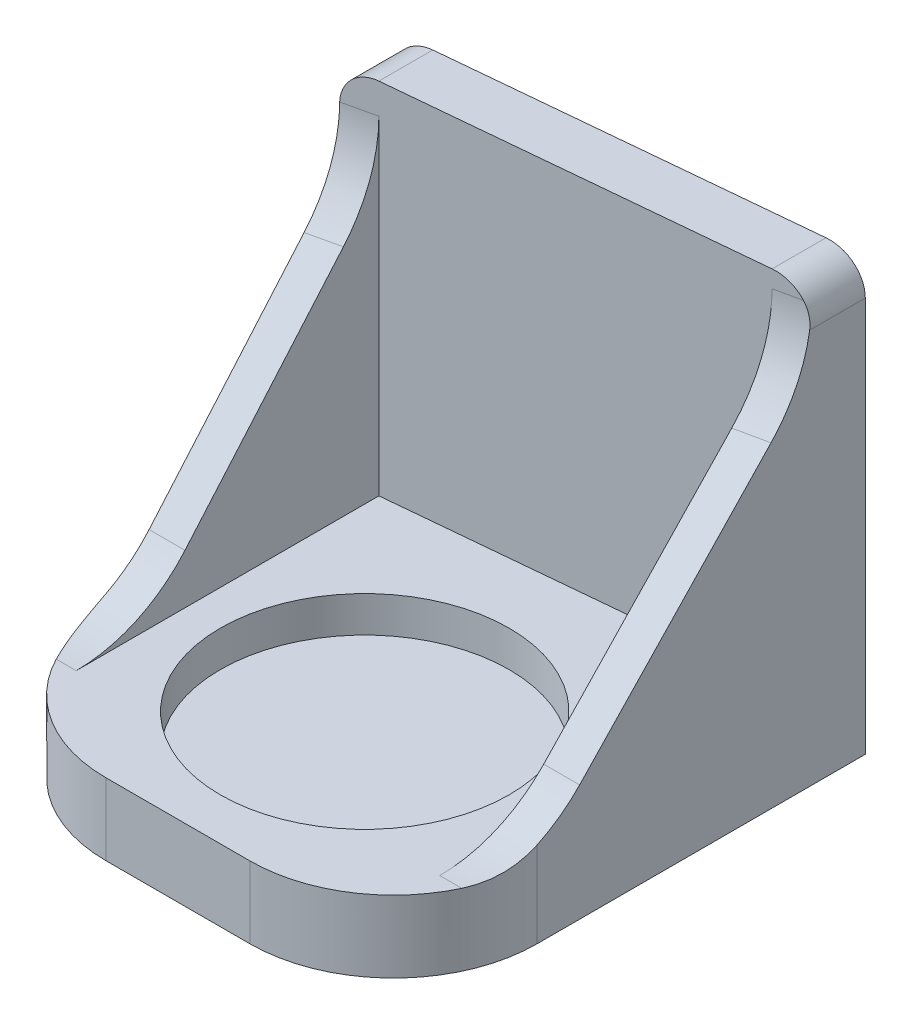
SolidWorks part; units mm, degrees
ref_plane "Front Plane" through (0, 0, 0) normal (0, 0, 1) x (1, 0, 0)
ref_plane "Top Plane" through (0, 0, 0) normal (0, 1, 0) x (1, 0, 0)
ref_plane "Right Plane" through (0, 0, 0) normal (1, 0, 0) x (0, 0, -1)
sketch "Sketch1" plane through (0, 0, 0) normal (0, 1, 0) x (1, 0, 0)
  line L0 (-19.05, 19.05) -> (-19.05, -19.05)
  line L1 (-19.05, -19.05) -> (19.05, -19.05)
  line L2 (19.05, -19.05) -> (19.05, 22.6515)
  line L3 (19.05, 22.6515) -> (-19.05, 19.05)
  point P4 (0, -19.05)
  point P5 (-19.05, 0)
  dimension "D1" = 5.4
  dimension "D2" = 38.1
extrude "Boss-Extrude1" add sketch "Sketch1" along normal blind 6.35
sketch "Sketch2" plane through (0, 6.35, 0) normal (0, 1, 0) x (1, 0, 0)
  circle A0 centre (0, -2.54) radius 12.7635
  point P3 (0, -2.9593)
  dimension "D1" = 25.527
  dimension "D2" = 2.54
extrude "Cut-Extrude1" cut sketch "Sketch2" against normal blind 3.175
sketch "Sketch3" plane through (0, 6.35, 0) normal (0, 1, 0) x (1, 0, 0)
  line L0 (19.05, 22.6515) -> (-19.05, 19.05) construction
  line L1 (19.05, 22.6515) -> (-19.05, 19.05)
  line L2 (-19.05, 19.05) -> (-19.05, 14.2875)
  line L3 (-19.05, 19.05) -> (-19.05, -19.05) construction
  line L4 (-19.05, 14.2875) -> (19.05, 17.889)
  line L5 (19.05, -19.05) -> (19.05, 22.6515) construction
  line L6 (19.05, 17.889) -> (19.05, 22.6515)
  dimension "D1" = 4.7625
extrude "Boss-Extrude2" add sketch "Sketch3" along normal blind 31.75
fillet "Fillet1" radius 12.7 2 edges at (19.05, 3.175, 19.05) (-19.05, 3.175, 19.05)
sketch "Sketch4" plane through (19.05, 0, 0) normal (1, 0, 0) x (0, 0, -1)
  line L0 (-6.35, 6.35) -> (17.889, 31.75)
  line L1 (17.889, 38.1) -> (17.889, 6.35) construction
  line L2 (17.889, 31.75) -> (17.889, 6.35)
  line L3 (17.889, 6.35) -> (-6.35, 6.35)
  point P6 (0, 0)
  point P8 (17.889, 38.1)
  point P9 (17.889, 33.9532)
  dimension "D1" = 25.4
extrude "Boss-Extrude3" add sketch "Sketch4" against normal blind 3.175
sketch "Sketch6" plane through (-19.05, 0, 0) normal (-1, 0, 0) x (0, 0, 1)
  line L0 (-15.5575, 31.75) -> (6.35, 6.35)
  line L2 (6.35, 6.35) -> (-15.5575, 6.35)
  line L3 (-15.5575, 6.35) -> (-15.5575, 31.75)
  line L4 (-14.2875, 38.1) -> (-14.2875, 6.35) construction
  point P2 (0, 0)
  dimension "D1" = 25.4
  dimension "D2" = 1.27
extrude "Boss-Extrude7" add sketch "Sketch6" against normal blind 3.175
fillet "Fillet2" radius 12.7 4 edges at (17.4625, 6.35, 6.35) (-17.4625, 6.35, 6.35) (17.4625, 31.5927, -17.7389) (-17.4625, 30.4515, -14.4376)
fillet "Fillet3" radius 3.175 2 edges at (19.05, 38.1, -20.2703) (-19.05, 38.1, -16.6688)
